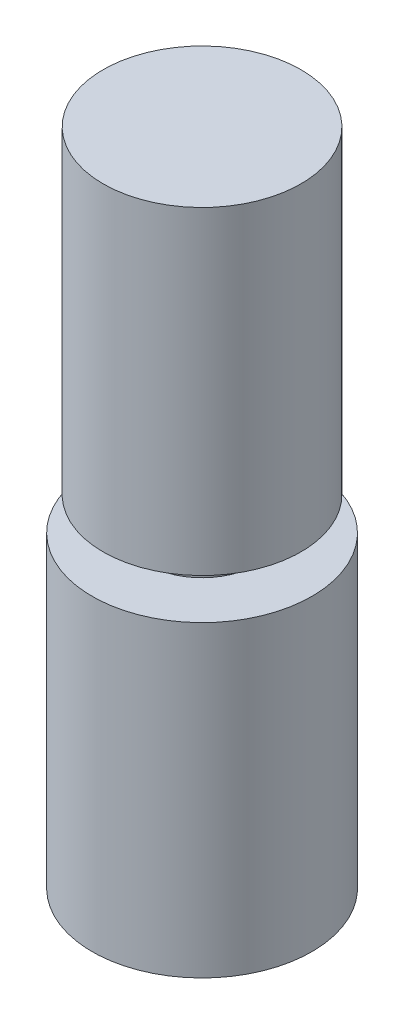
SolidWorks part; units mm, degrees
ref_plane "前视基准面" through (0, 0, 0) normal (0, 0, 1) x (1, 0, 0)
ref_plane "上视基准面" through (0, 0, 0) normal (0, 1, 0) x (1, 0, 0)
ref_plane "右视基准面" through (0, 0, 0) normal (1, 0, 0) x (0, 0, -1)
other "Configuration Table"
sketch "草图1" plane through (0, 0, 0) normal (0, 0, 1) x (1, 0, 0)
  line L0 (0, 0) -> (0, 120)
  line L1 (0, 120) -> (-18, 120)
  line L2 (-18, 120) -> (-18, 62)
  line L3 (-18, 62) -> (-10, 62)
  line L4 (-10, 62) -> (-10, 56)
  line L5 (-10, 56) -> (-20, 56)
  line L6 (-20, 56) -> (-20, 0)
  line L7 (-20, 0) -> (0, 0)
  point P10 (-15, 56)
  dimension "D1" = 18
  dimension "D2" = 64
  dimension "D3" = 120
  dimension "D4" = 20
  dimension "D5" = 6
  dimension "D6" = 5
revolve "旋转2" add sketch "草图1" angle 360 about L0
sketch "草图2" plane through (0, 0, 0) normal (0, -1, 0) x (1, 0, 0)
  line L0 (24.75, 0) -> (-24.75, 0) construction
  circle A0 centre (0, 0) radius 22.5
  dimension "D1" = 45
